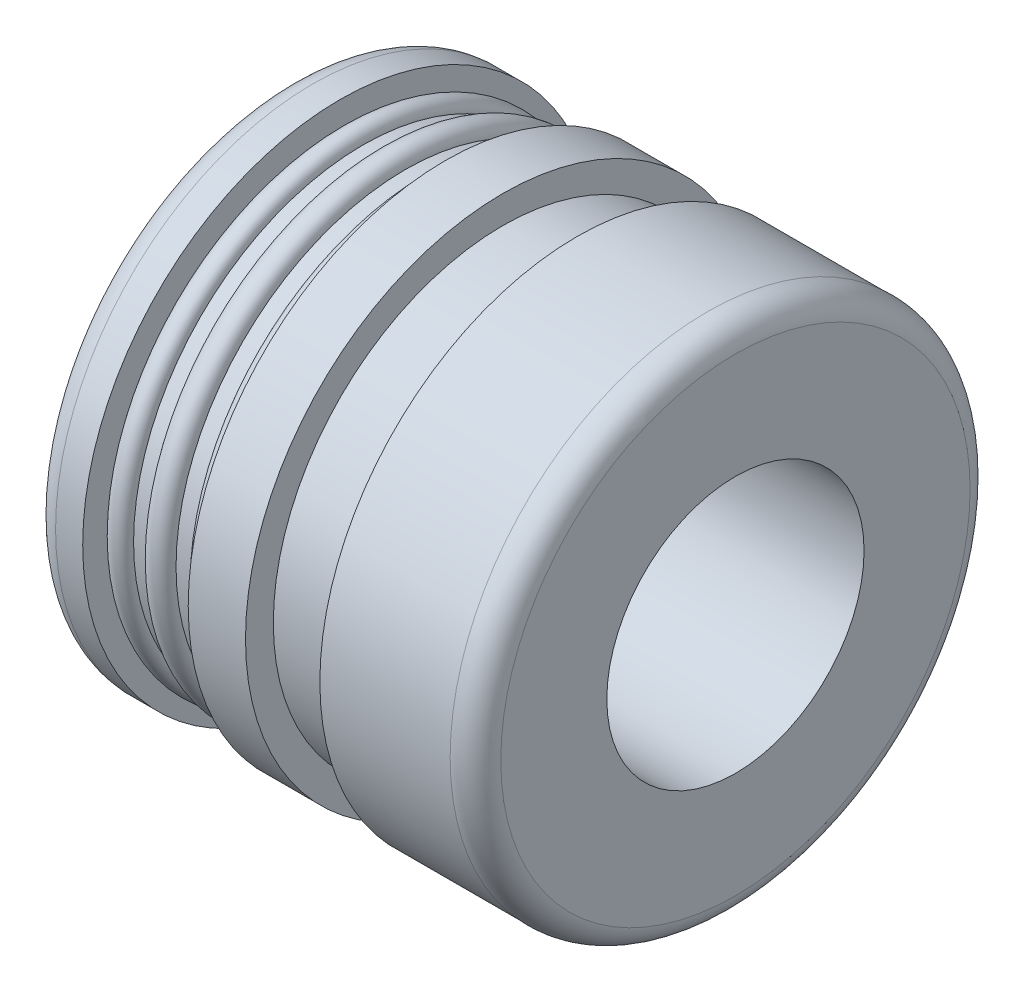
SolidWorks part; units mm, degrees
material "1060 Alloy"
ref_plane "Front Plane" through (0, 0, 0) normal (0, 0, 1) x (1, 0, 0)
ref_plane "Top Plane" through (0, 0, 0) normal (0, 1, 0) x (1, 0, 0)
ref_plane "Right Plane" through (0, 0, 0) normal (1, 0, 0) x (0, 0, -1)
sketch "Sketch1" plane through (0, 0, 0) normal (0, 0, 1) x (1, 0, 0)
  line L5 (-7.7391, 12.7) -> (-9.0786, 12.7)
  line L8 (3.9688, 12.7) -> (3.9688, 11.3266)
  line L9 (3.9688, 11.3266) -> (0.2977, 11.3266)
  line L10 (0.2977, 11.3266) -> (0.2977, 12.7)
  line L11 (0.2977, 12.7) -> (-2.5301, 12.7)
  line L12 (-2.5301, 12.7) -> (-2.5301, 11.3266)
  line L13 (-2.5301, 11.3266) -> (-2.5741, 11.3266)
  line L14 (-7.7391, 11.3266) -> (-7.7391, 12.7)
  line L15 (-7.7391, 12.7) -> (-9.0786, 12.7)
  line L16 (-10.3124, 6.35) -> (-10.3124, 11.3266)
  line L17 (0.2977, 12.7) -> (-2.5301, 12.7)
  line L18 (11.7856, 11.5839) -> (11.7856, 6.35)
  line L19 (11.7856, 6.35) -> (-10.3124, 6.35)
  line L20 (0, 0) -> (-2.9205, 0)
  line L21 (-5.7649, 11.3266) -> (-6.6016, 11.3266)
  line L22 (-3.5983, 11.3266) -> (-4.5043, 11.3266)
  line L23 (-7.6802, 11.3266) -> (-7.7391, 11.3266)
  line L24 (10.401, 12.7) -> (3.9688, 12.7)
  arc A1 (-10.3124, 11.3266) -> (-9.0786, 12.7) centre (-9.0088, 11.3964) cw
  arc A2 (11.7856, 11.5839) -> (10.401, 12.7) centre (10.5353, 11.4497) ccw
  arc A3 (-2.5741, 11.3266) -> (-3.5983, 11.3266) centre (-3.0862, 11.3266) ccw
  arc A4 (-4.5043, 11.3266) -> (-5.7649, 11.3266) centre (-5.1346, 11.3266) ccw
  arc A5 (-6.6016, 11.3266) -> (-7.6802, 11.3266) centre (-7.1409, 11.3266) ccw
  point P0 (0, 0)
revolve "Revolve1" add sketch "Sketch1" angle 360 about L20
